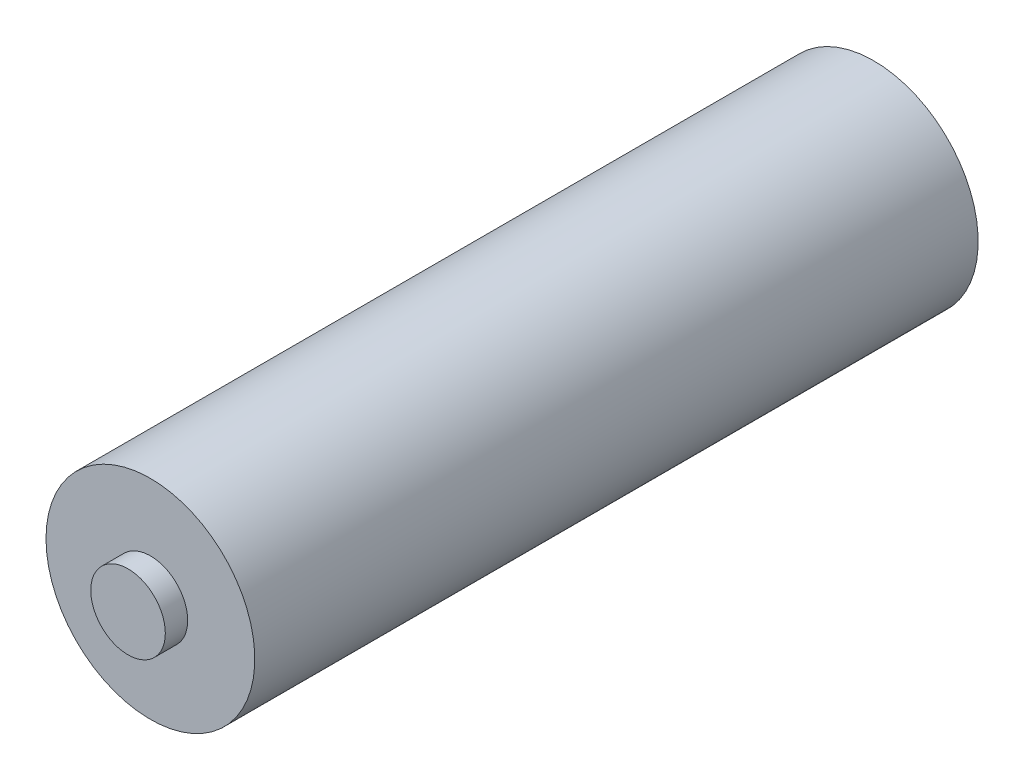
SolidWorks part; units mm, degrees
ref_plane "Alzado" through (0, 0, 0) normal (0, 0, 1) x (1, 0, 0)
ref_plane "Planta" through (0, 0, 0) normal (0, 1, 0) x (1, 0, 0)
ref_plane "Vista lateral" through (0, 0, 0) normal (1, 0, 0) x (0, 0, -1)
sketch "Croquis1" plane through (0, 0, 0) normal (0, 0, 1) x (1, 0, 0)
  circle A0 centre (0, 0) radius 7
  dimension "D1" = 14
extrude "Saliente-Extruir1" add sketch "Croquis1" along normal blind 48.5
sketch "Croquis2" plane through (0, 0, 48.5) normal (0, 0, 1) x (1, 0, 0)
  circle A0 centre (0, 0) radius 2.5
  dimension "D1" = 5
extrude "Saliente-Extruir2" add sketch "Croquis2" along normal blind 1.5
